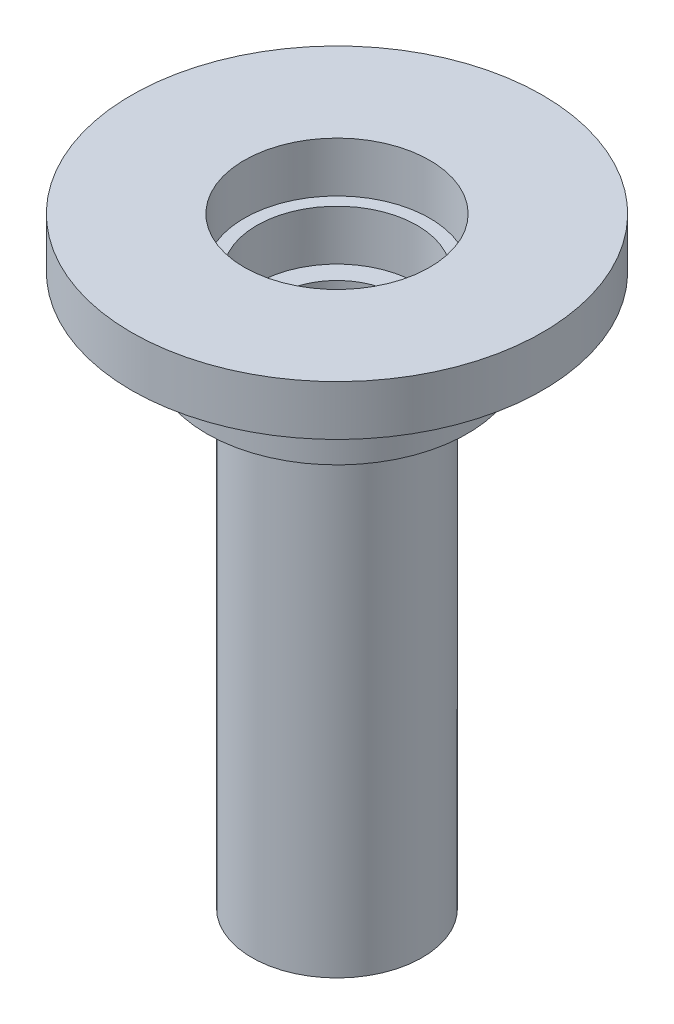
SolidWorks part; units mm, degrees
ref_plane "前视基准面" through (0, 0, 0) normal (0, 0, 1) x (1, 0, 0)
ref_plane "上视基准面" through (0, 0, 0) normal (0, 1, 0) x (1, 0, 0)
ref_plane "右视基准面" through (0, 0, 0) normal (1, 0, 0) x (0, 0, -1)
sketch "Sketch2" plane through (0, 0, 0) normal (0, 0, 1) x (1, 0, 0)
  line L0 (0, 0) -> (0, 120)
  line L1 (0, 120) -> (4, 120)
  line L2 (4, 120) -> (4, 140)
  line L3 (4, 140) -> (29, 140)
  line L4 (29, 140) -> (29, 130)
  line L5 (29, 130) -> (14, 130)
  line L6 (14, 130) -> (14, 115)
  line L8 (14, 115) -> (5, 115)
  line L9 (5, 115) -> (5, 0)
  line L10 (5, 0) -> (0, 0)
  line L11 (-12, -9.3797) -> (-12, 228.3801) construction
  dimension "D1" = 120
  dimension "D2" = 20
  dimension "D3" = 25
  dimension "D4" = 10
  dimension "D5" = 15
  dimension "D6" = 32
  dimension "D7" = 5
  dimension "D8" = 15
  dimension "D9" = 12
  dimension "D10" = 24
  dimension "D11" = 34
revolve "Revolve1" add sketch "Sketch2" angle 360 about L11
sketch "Sketch3" plane through (0, 0, 0) normal (0, -1, 0) x (1, 0, 0)
  circle A0 centre (-12, 0) radius 18.5
  dimension "D1" = 37
extrude "Extrude1" cut sketch "Sketch3" against normal blind 20
sketch "Sketch4" plane through (0, 20, 0) normal (0, -1, 0) x (1, 0, 0)
  circle A0 centre (-12, 0) radius 14
  circle A1 centre (-12, 0) radius 12 construction
  dimension "D1" = 2
extrude "Extrude2" cut sketch "Sketch4" against normal blind 14
sketch "Sketch5" plane through (0, 140, 0) normal (0, 1, 0) x (1, 0, 0)
  circle A0 centre (-12, 0) radius 18.5
  dimension "D1" = 37
extrude "Extrude3" cut sketch "Sketch5" against normal blind 10
